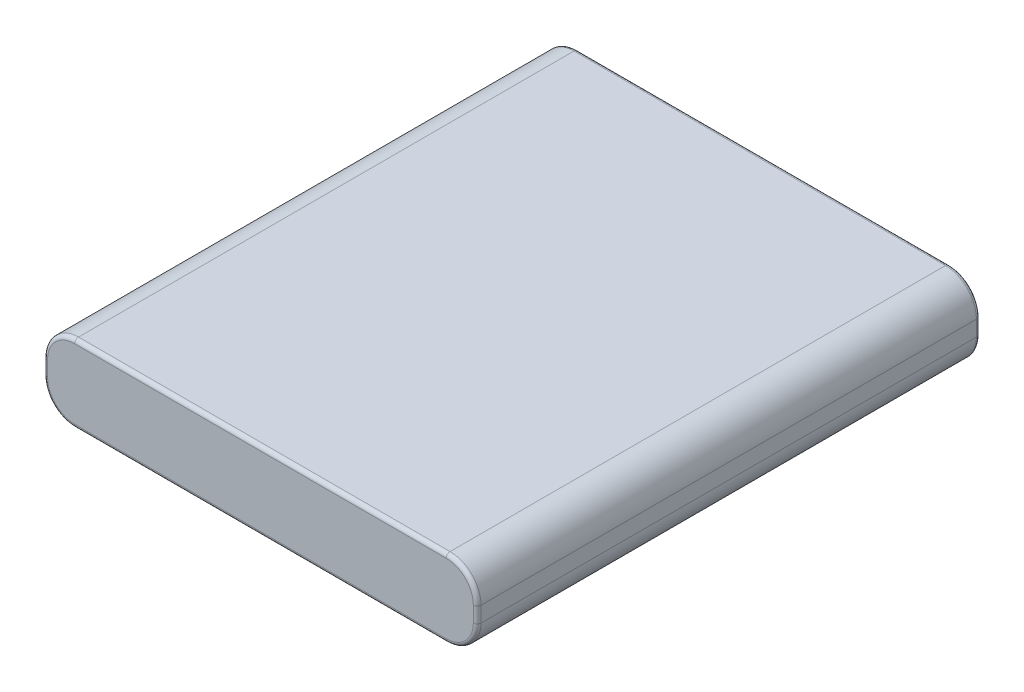
SolidWorks part; units mm, degrees
ref_plane "前视基准面" through (0, 0, 0) normal (0, 0, 1) x (1, 0, 0)
ref_plane "上视基准面" through (0, 0, 0) normal (0, 1, 0) x (1, 0, 0)
ref_plane "右视基准面" through (0, 0, 0) normal (1, 0, 0) x (0, 0, -1)
sketch "草图1" plane through (0, 0, 0) normal (0, 1, 0) x (1, 0, 0)
  line L1 (-28, 32.5) -> (28, 32.5)
  line L2 (-28, 32.5) -> (-28, -32.5)
  line L3 (-28, -32.5) -> (28, -32.5)
  line L4 (28, 32.5) -> (28, -32.5)
  line L5 (-28, 32.5) -> (28, -32.5) construction
  line L6 (-28, -32.5) -> (28, 32.5) construction
  point P0 (0, 0)
  dimension "D1" = 56
  dimension "D2" = 65
extrude "凸台-拉伸1" add sketch "草图1" along normal blind 10
fillet "圆角1" radius 4 4 edges at (-28, 0, 0) (28, 0, 0) (28, 10, 0) (-28, 10, 0)
fillet "圆角2" radius 0.5 16 edges at (26.8284, 1.1716, -32.5) (28, 5, -32.5) (26.8284, 8.8284, -32.5) (0, 10, -32.5) (-26.8284, 8.8284, -32.5) (-28, 5, -32.5) (-26.8284, 1.1716, -32.5) (0, 0, -32.5) (-26.8284, 8.8284, 32.5) (0, 10, 32.5) (26.8284, 8.8284, 32.5) (28, 5, 32.5) (26.8284, 1.1716, 32.5) (0, 0, 32.5) (-26.8284, 1.1716, 32.5) (-28, 5, 32.5)
sketch "草图2" plane through (0, 0, 0) normal (0, -1, 0) x (1, 0, 0)
  circle A0 centre (0, 6.1058) radius 7
  dimension "D1" = 14
extrude "凸台-拉伸2" add sketch "草图2" along normal blind 2
